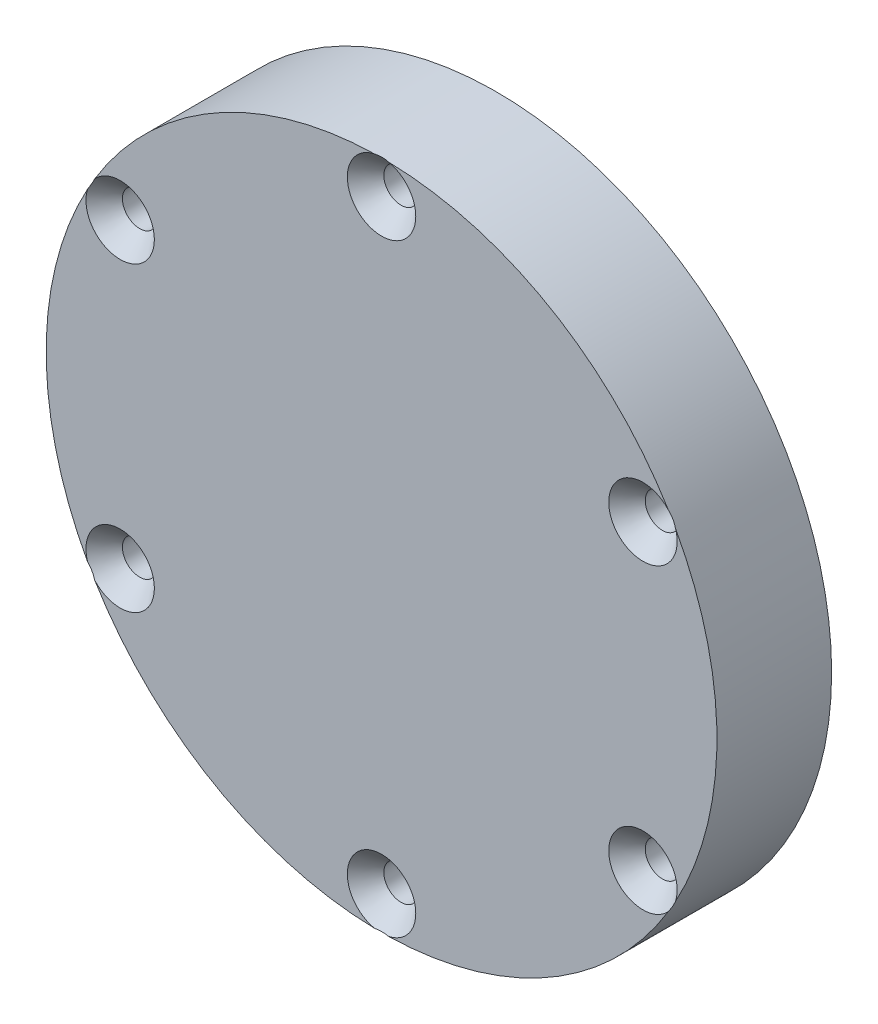
SolidWorks part; units mm, degrees
material "6061-T6 (SS)"
ref_plane "Front Plane" through (0, 0, 0) normal (0, 0, 1) x (1, 0, 0)
ref_plane "Top Plane" through (0, 0, 0) normal (0, 1, 0) x (1, 0, 0)
ref_plane "Right Plane" through (0, 0, 0) normal (1, 0, 0) x (0, 0, -1)
sketch "Sketch1" plane through (0, 0, 0) normal (0, 0, 1) x (1, 0, 0)
  circle A0 centre (0, 0) radius 31.75
  dimension "D1" = 63.5
extrude "Boss-Extrude1" add sketch "Sketch1" along normal blind 10.8585
hole_wizard "CSK for #4 Flat Head Socket Cap Screw1" positions "Sketch3" profile "Sketch2" countersink size "#4" standard "Ansi Inch" end condition through all
sketch "Sketch3" plane through (0, 0, 10.8585) normal (0, 0, 1) x (1, 0, 0)
  line L0 (0, 0) -> (0, 28.575) construction
  point P0 (0, 28.575)
  dimension "D1" = 28.575
sketch "Sketch2" plane through (0, 28.575, 10.8585) normal (1, 0, 0) x (0, -1, 0)
  line L0 (0, 0) -> (0, 10.8585)
  line L1 (0, 10.8585) -> (1.6319, 10.8585)
  line L2 (1.6319, 10.8585) -> (1.6319, 1.8481)
  line L3 (1.6319, 1.8481) -> (3.2385, 0)
  line L5 (3.2385, 0) -> (0, 0)
  line L6 (-1.6319, 1.8481) -> (-3.2385, 0) construction
  line L11 (0, -6.35) -> (0, 107.95) construction
  dimension "Thru Hole Dia." = 3.2639
  dimension "Thru Hole Depth" = 10.8585
  dimension "Near C'Sink Dia." = 6.477
  dimension "Near C'Sink Angle" = 82
pattern_circular "CirPattern1" count 6 over 360 about axis through (0, 0, 0) along (0, 0, 1) of "CSK for #4 Flat Head Socket Cap Screw1"
sketch "Sketch4" plane through (0, 0, 0) normal (0, 0, -1) x (-1, 0, 0)
  circle A3 centre (0, 0) radius 29.3687
  arc A4 (-3.1585, 29.1984) -> (-23.7073, 17.3346) centre (0, 0) ccw
  arc A38 (23.7073, 17.3346) -> (26.8658, 11.8639) centre (24.7467, 14.2875) ccw
  circle A39 centre (0, 28.575) radius 3.2194
  arc A40 (-3.1585, 29.1984) -> (3.1585, 29.1984) centre (0, 28.575) ccw
  arc A41 (26.8658, -11.8639) -> (23.7073, -17.3346) centre (24.7467, -14.2875) ccw
  arc A42 (3.1585, -29.1984) -> (-3.1585, -29.1984) centre (0, -28.575) ccw
  arc A43 (-23.7073, -17.3346) -> (-26.8658, -11.8639) centre (-24.7467, -14.2875) ccw
  arc A44 (-26.8658, 11.8639) -> (-23.7073, 17.3346) centre (-24.7467, 14.2875) ccw
  arc A45 (23.7073, 17.3346) -> (3.1585, 29.1984) centre (0, 0) ccw
  arc A46 (26.8658, -11.8639) -> (26.8658, 11.8639) centre (0, 0) ccw
  arc A47 (3.1585, -29.1984) -> (23.7073, -17.3346) centre (0, 0) ccw
  arc A48 (-23.7073, -17.3346) -> (-3.1585, -29.1984) centre (0, 0) ccw
  arc A49 (-26.8658, 11.8639) -> (-26.8658, -11.8639) centre (0, 0) ccw
  dimension "D1" = 2.3813
  dimension "D2" = 1.5875
  dimension "D3" = 6
extrude "Cut-Extrude1" cut sketch "Sketch4" against normal blind 8.4772
fillet "Fillet1" radius 3.175 12 edges at (3.1585, 29.1984, 4.2386) (-3.1585, 29.1984, 4.2386) (-23.7073, 17.3346, 4.2386) (-26.8658, 11.8639, 4.2386) (-26.8658, -11.8639, 4.2386) (-23.7073, -17.3346, 4.2386) (-3.1585, -29.1984, 4.2386) (3.1585, -29.1984, 4.2386) (23.7073, -17.3346, 4.2386) (26.8658, -11.8639, 4.2386) (23.7073, 17.3346, 4.2386) (26.8658, 11.8639, 4.2386)
sketch "Sketch5" plane through (0, 0, 8.4772) normal (0, 0, -1) x (-1, 0, 0)
  circle A0 centre (0, 0) radius 4.7625
  dimension "D1" = 9.525
extrude "Cut-Extrude2" cut sketch "Sketch5" against normal blind 1.5875
